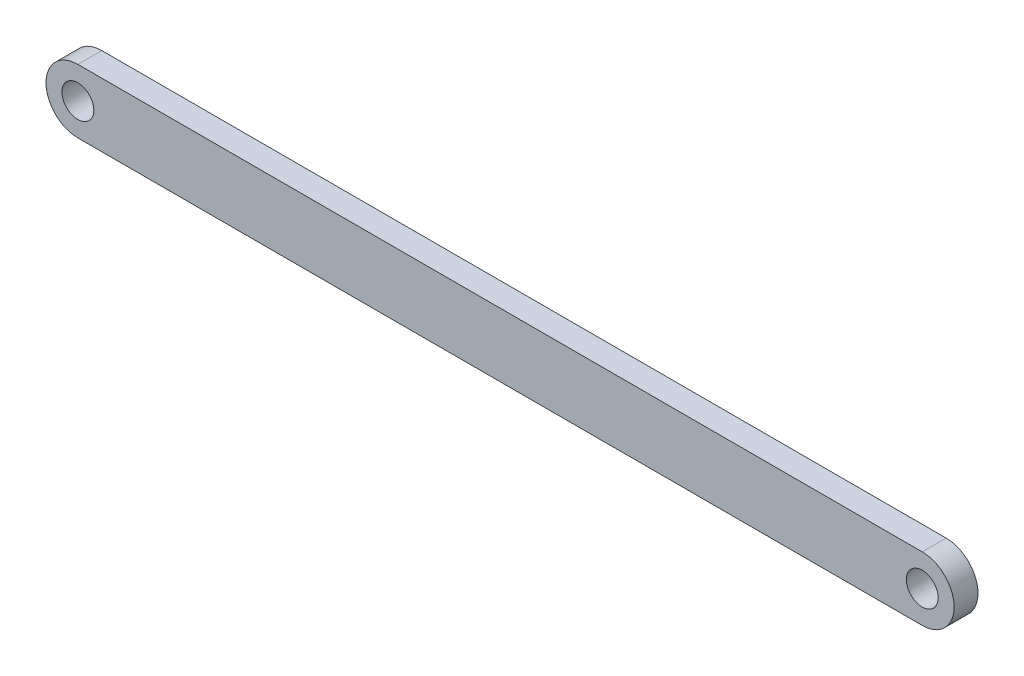
SolidWorks part; units mm, degrees
material "Thornel Mat VMA"
ref_plane "前视基准面" through (0, 0, 0) normal (0, 0, 1) x (1, 0, 0)
ref_plane "上视基准面" through (0, 0, 0) normal (0, 1, 0) x (1, 0, 0)
ref_plane "右视基准面" through (0, 0, 0) normal (1, 0, 0) x (0, 0, -1)
sketch "草图1" plane through (0, 0, 0) normal (0, 0, 1) x (1, 0, 0)
  line L0 (-106, 0) -> (106, 0) construction
  line L1 (-106, 0) -> (106, 0) construction
  line L2 (-106, 8) -> (106, 8)
  line L3 (-106, -8) -> (106, -8)
  circle A0 centre (106, 0) radius 4
  circle A1 centre (-106, 0) radius 4
  arc A2 (-106, 8) -> (-106, -8) centre (-106, 0) ccw
  arc A3 (106, -8) -> (106, 8) centre (106, 0) ccw
  point P4 (0, 0)
  point P7 (0, 0)
  dimension "D2" = 8
  dimension "D3" = 4
  dimension "D1" = 212
extrude "凸台-拉伸1" add sketch "草图1" along normal blind 6
